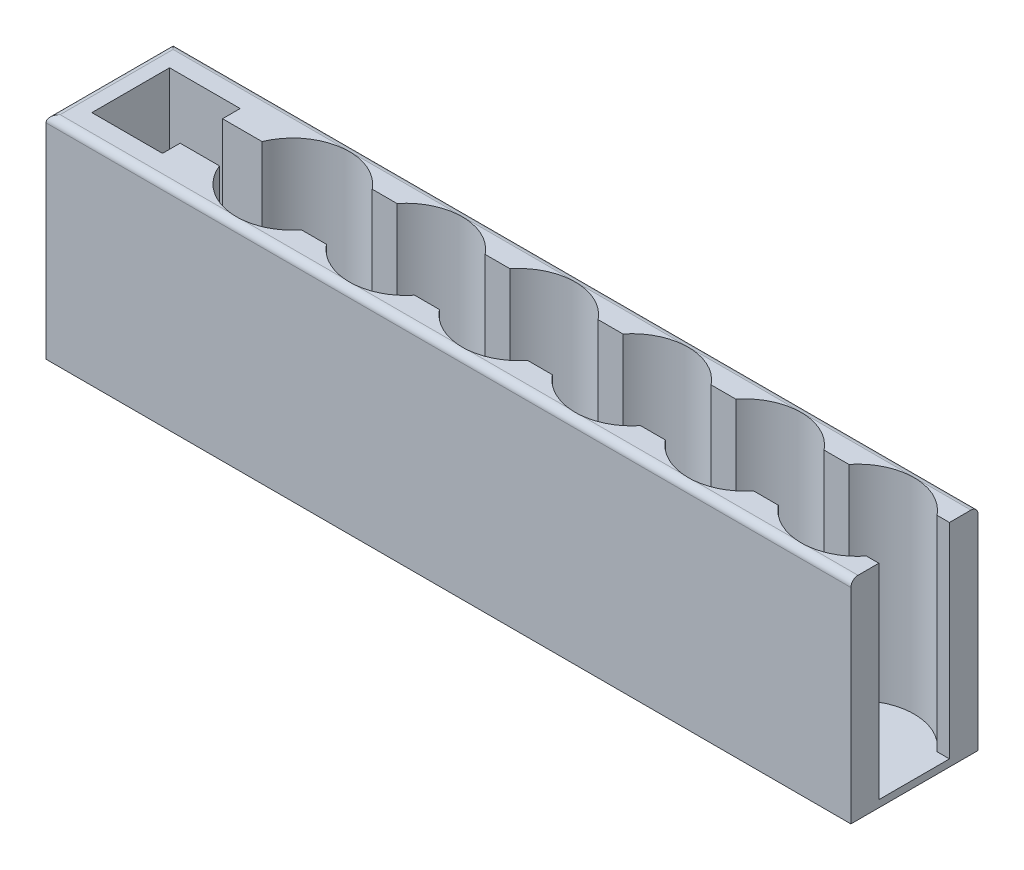
SolidWorks part; units mm, degrees
ref_plane "Front Plane" through (0, 0, 0) normal (0, 0, 1) x (1, 0, 0)
ref_plane "Top Plane" through (0, 0, 0) normal (0, 1, 0) x (1, 0, 0)
ref_plane "Right Plane" through (0, 0, 0) normal (1, 0, 0) x (0, 0, -1)
sketch "Sketch1" plane through (0, 0, 0) normal (0, 1, 0) x (1, 0, 0)
  line L1 (-57, 9) -> (57, 9)
  line L2 (-57, 9) -> (-57, -9)
  line L3 (-57, -9) -> (57, -9)
  line L4 (57, 9) -> (57, -9)
  line L5 (-57, 9) -> (57, -9) construction
  line L6 (-57, -9) -> (57, 9) construction
  point P0 (0, 0)
  dimension "D1" = 18
  dimension "D2" = 114
extrude "Boss-Extrude1" add sketch "Sketch1" along normal blind 30
sketch "Sketch2" plane through (0, 30, 0) normal (0, 1, 0) x (1, 0, 0)
  line L0 (57, -9) -> (57, 9) construction
  line L1 (-31, 4.958) -> (49, 4.958)
  line L2 (-31, 4.958) -> (-31, -5.042)
  line L3 (49, 4.958) -> (58.7063, 4.958)
  line L4 (-31, -5.042) -> (49, -5.042)
  line L5 (58.7063, 4.958) -> (58.7063, -5.042)
  line L6 (58.7063, -5.042) -> (49, -5.042)
  circle A0 centre (-31, -0.042) radius 8
  circle A1 centre (-15, -0.042) radius 8
  circle A2 centre (1, -0.042) radius 8
  circle A3 centre (17, -0.042) radius 8
  circle A4 centre (33, -0.042) radius 8
  circle A5 centre (49, -0.042) radius 8
  point P12 (9, -0.042)
  dimension "D2" = 16
  dimension "D3" = 16
  dimension "D4" = 16
  dimension "D5" = 16
  dimension "D6" = 16
  dimension "D7" = 16
  dimension "D8" = 16
  dimension "D9" = 10
  dimension "D10" = 16
  dimension "D11" = 16
  dimension "D12" = 16
  dimension "D13" = 16
  dimension "D14" = 8
  dimension "D15" = 0
extrude "Cut-Extrude2" cut sketch "Sketch2" against normal blind 29
sketch "Sketch4" plane through (0, 30, 0) normal (0, 1, 0) x (1, 0, 0)
  line L1 (-44, 3) -> (-38, 3)
  line L2 (-44, 3) -> (-44, -3)
  line L3 (-44, -3) -> (-38, -3)
  line L4 (-38, 3) -> (-38, -3)
  line L5 (-44, 3) -> (-38, -3) construction
  line L6 (-44, -3) -> (-38, 3) construction
  line L7 (57, 9) -> (-57, 9) construction
  arc A1 (-24.755, 4.958) -> (-24.755, -5.042) centre (-31, -0.042) ccw construction
  point P0 (-41, 0)
  point P14 (-39, -0.042)
  dimension "D1" = 6
  dimension "D2" = 6
  dimension "D3" = 1
  dimension "D4" = 6
extrude "Cut-Extrude4" cut sketch "Sketch4" against normal blind 29
fillet "Fillet1" radius 1 3 edges at (-57, 30, 0) (0, 30, -9) (0, 30, 9)
sketch "Sketch5" plane through (0, 30, 0) normal (0, 1, 0) x (1, 0, 0)
  line L0 (-44, 3) -> (-44, -3) construction
  line L1 (-54, 5.5) -> (-44, 5.5)
  line L2 (-54, 5.5) -> (-54, -5.5)
  line L3 (-54, -5.5) -> (-44, -5.5)
  line L4 (-44, 5.5) -> (-44, -5.5)
  line L5 (-54, 5.5) -> (-44, -5.5) construction
  line L6 (-54, -5.5) -> (-44, 5.5) construction
  point P0 (-49, 0)
  dimension "D1" = 11
  dimension "D2" = 0
  dimension "D3" = 0
  dimension "D4" = 10
extrude "Cut-Extrude6" cut sketch "Sketch5" against normal blind 29
